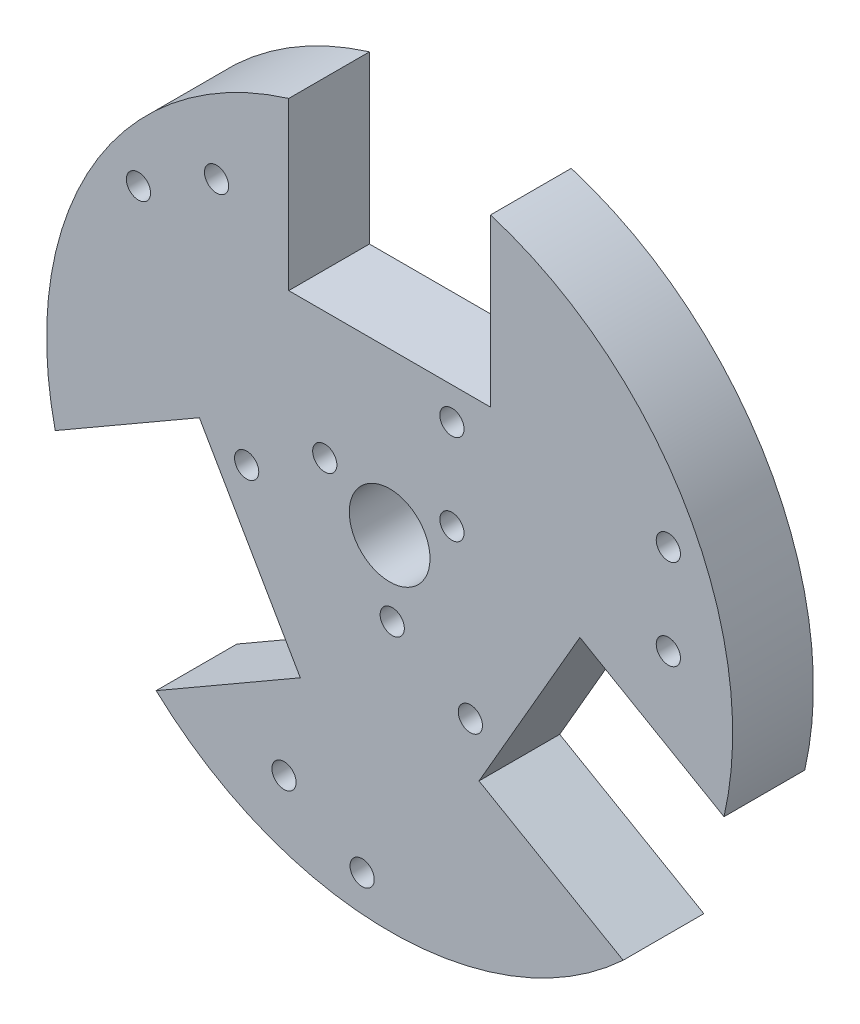
SolidWorks part; units mm, degrees
ref_plane "Front Plane" through (0, 0, 0) normal (0, 0, 1) x (1, 0, 0)
ref_plane "Top Plane" through (0, 0, 0) normal (0, 1, 0) x (1, 0, 0)
ref_plane "Right Plane" through (0, 0, 0) normal (1, 0, 0) x (0, 0, -1)
sketch "Plan" plane through (0, 0, 0) normal (0, 0, 1) x (1, 0, 0)
  line L0 (0, 0) -> (0, 60) construction
  line L1 (0, 0) -> (51.9615, -30) construction
  line L2 (0, 0) -> (-51.9615, -30) construction
  line L3 (0, 0) -> (0, 60) construction
  line L4 (0, 0) -> (51.9615, -30) construction
  line L5 (42.3527, 42.5) -> (-42.3527, 42.5) construction
  line L6 (-10, 60) -> (10, 60)
  line L7 (-10, 60) -> (-10, 25)
  line L8 (-10, 25) -> (10, 25)
  line L9 (10, 60) -> (10, 25)
  circle A0 centre (0, 0) radius 60
  text T0 "Tyre"
  point P13 (0, 60)
  point P17 (-10, 42.5)
  dimension "D1" = 3
  dimension "D5" = 120
  dimension "D2" = 120
  dimension "D3" = 35
  dimension "D4" = 20
sketch "Stepper Motor" plane through (0, 0, 0) normal (0, 0, 1) x (1, 0, 0)
  line L1 (10.7429, 49.5) -> (29.7429, 49.5)
  line L2 (10.7429, 49.5) -> (10.7429, 21.5)
  line L3 (10.7429, 21.5) -> (29.7429, 21.5)
  line L4 (29.7429, 49.5) -> (29.7429, 21.5)
  line L5 (10.7429, 47) -> (0.7429, 47)
  line L6 (10.7429, 47) -> (10.7429, 38)
  line L7 (10.7429, 38) -> (0.7429, 38)
  line L8 (0.7429, 47) -> (0.7429, 38)
  line L9 (-1.5598, 42.5) -> (29.7429, 42.5) construction
  line L11 (42.3527, 42.5) -> (-42.3527, 42.5) construction
  text T0 "Stepper"
  point P11 (0.7429, 42.5)
  dimension "D1" = 28
  dimension "D2" = 19
  dimension "D3" = 9
  dimension "D4" = 10
  dimension "D5" = 2.5
sketch "DC Motor" plane through (0, 0, 0) normal (0, 0, 1) x (1, 0, 0)
  line L0 (63.4697, 76.7537) -> (25.6249, 76.7537) construction
  line L1 (38.6689, 84.3037) -> (63.6689, 84.3037)
  line L2 (38.6689, 84.3037) -> (38.6689, 69.2037)
  line L3 (38.6689, 69.2037) -> (63.6689, 69.2037)
  line L4 (63.6689, 84.3037) -> (63.6689, 69.2037)
  line L5 (28.6689, 79.8287) -> (38.6689, 79.8287)
  line L6 (28.6689, 79.8287) -> (28.6689, 73.6787)
  line L7 (28.6689, 73.6787) -> (38.6689, 73.6787)
  line L8 (38.6689, 79.8287) -> (38.6689, 73.6787)
  text T0 "DC"
  point P10 (38.6689, 76.7537)
  point P11 (38.6689, 76.7537)
  dimension "D1" = 25
  dimension "D2" = 15.1
  dimension "D3" = 10
  dimension "D4" = 6.15
sketch "Sketch4" plane through (0, 0, 0) normal (0, 0, 1) x (1, 0, 0)
  circle A0 centre (0, 0) radius 42.5
  dimension "D1" = 85
extrude "base" add sketch "Sketch4" along normal blind 10
sketch "Sketch5" plane through (0, 0, 0) normal (0, 0, 1) x (1, 0, 0)
  line L0 (0, 0) -> (0, 60) construction
  line L1 (12.5, 20) -> (-12.5, 20)
  line L2 (12.5, 20) -> (12.5, 60)
  line L3 (12.5, 60) -> (-12.5, 60)
  line L4 (-12.5, 20) -> (-12.5, 60)
  line L5 (11.0705, -20.8253) -> (23.5705, 0.8253)
  line L6 (23.5705, 0.8253) -> (58.2115, -19.1747)
  line L7 (11.0705, -20.8253) -> (45.7115, -40.8253)
  line L8 (45.7115, -40.8253) -> (58.2115, -19.1747)
  line L9 (-23.5705, 0.8253) -> (-11.0705, -20.8253)
  line L10 (-11.0705, -20.8253) -> (-45.7115, -40.8253)
  line L11 (-23.5705, 0.8253) -> (-58.2115, -19.1747)
  line L12 (-58.2115, -19.1747) -> (-45.7115, -40.8253)
  circle A0 centre (0, 0) radius 5
  point P4 (0, 20)
  point P7 (0, 60)
  point P19 (0, 0)
  dimension "D1" = 25
  dimension "D2" = 40
  dimension "D4" = 20
  dimension "D3" = 3
extrude "Tyre cut" cut sketch "Sketch5" along normal blind 10
sketch "arm" plane through (0, 0, 0) normal (0, 0, 1) x (1, 0, 0)
  line L0 (-12.5, 20) -> (12.5, 20) construction
  line L1 (12.5, 49.5) -> (29.7429, 49.5)
  line L2 (12.5, 49.5) -> (12.5, 0.8253)
  line L3 (12.5, 0.8253) -> (29.7429, 0.8253)
  line L4 (29.7429, 49.5) -> (29.7429, 0.8253)
  line L5 (4.9314, 20) -> (37.5, 20)
  line L6 (12.5, 20) -> (12.5, 40.6202) construction
  line L7 (29.7429, 49.5) -> (29.7429, 21.5) construction
  line L8 (10.7429, 49.5) -> (29.7429, 49.5) construction
  line L9 (-5.5353, -11.238) -> (-14.1567, -26.1707)
  line L10 (27.9968, -50.5081) -> (-14.1567, -26.1707)
  line L11 (36.6183, -35.5753) -> (-5.5353, -11.238)
  line L12 (36.6183, -35.5753) -> (27.9968, -50.5081)
  line L13 (-6.9647, 10.4127) -> (-15.5862, 25.3454)
  line L14 (-57.7397, 1.0081) -> (-15.5862, 25.3454)
  line L15 (-49.1183, -13.9247) -> (-6.9647, 10.4127)
  line L16 (-49.1183, -13.9247) -> (-57.7397, 1.0081)
  line L17 (4.9314, 20) -> (4.9314, 0.8253)
  line L18 (4.9314, 0.8253) -> (37.5, 0.8253)
  line L19 (37.5, 20) -> (37.5, 0.8253)
  line L20 (14.8548, -14.2707) -> (-1.751, -4.6834)
  line L21 (-1.751, -4.6834) -> (-18.0353, -32.8886)
  line L22 (14.8548, -14.2707) -> (-1.4295, -42.476)
  line L23 (-1.4295, -42.476) -> (-18.0353, -32.8886)
  line L24 (-19.7862, -5.7293) -> (-3.1805, 3.8581)
  line L25 (-3.1805, 3.8581) -> (-19.4647, 32.0633)
  line L26 (-19.7862, -5.7293) -> (-36.0705, 22.476)
  line L27 (-36.0705, 22.476) -> (-19.4647, 32.0633)
  line L29 (10.5, 20) -> (31.7429, 20)
  line L30 (10.5, 20) -> (10.5, 0.8253)
  line L31 (10.5, 0.8253) -> (31.7429, 0.8253)
  line L32 (31.7429, 20) -> (31.7429, 0.8253)
  line L33 (12.0705, -19.0933) -> (-4.5353, -9.5059)
  line L34 (1.4491, -37.4901) -> (-15.1567, -27.9028)
  line L35 (-22.5705, -0.9067) -> (-5.9647, 8.6806)
  line L36 (-33.1919, 17.4901) -> (-16.5862, 27.0775)
  circle A0 centre (0, 0) radius 5 construction
  arc A1 (41.4281, -9.4848) -> (12.5, 40.6202) centre (0, 0) ccw construction
  point P21 (0, 0)
  point P37 (0, 0)
  point P50 (0, 0)
  dimension "D5" = 2
  dimension "D6" = 2
  dimension "D1" = 3
  dimension "D4" = 3
  dimension "D7" = 3
sketch "Sketch6" plane through (0, 0, 0) normal (0, 0, 1) x (1, 0, 0)
  line L1 (21.1214, 16.9548) -> (21.1214, 5.6527) construction
  line L2 (4.9314, 18.6632) -> (10.5, 18.6632) construction
  line L3 (4.9314, 20) -> (4.9314, 0.8253) construction
  line L4 (10.5, 20) -> (10.5, 0.8253) construction
  line L5 (4.9314, 20) -> (37.5, 20) construction
  line L6 (4.9314, 0.8253) -> (37.5, 0.8253) construction
  line L7 (12.5, 0.8253) -> (29.7429, 0.8253) construction
  circle A0 centre (7.7157, 16) radius 1.5
  circle A1 centre (7.7157, 4.8253) radius 1.5
  circle A2 centre (34.5272, 4.8253) radius 1.5
  circle A3 centre (34.5272, 16) radius 1.5
  circle A4 centre (9.9986, -14.682) radius 1.5
  circle A5 centre (0.321, -9.0947) radius 1.5
  circle A6 centre (-13.0847, -32.3141) radius 1.5
  circle A7 centre (-3.4072, -37.9014) radius 1.5
  circle A8 centre (-17.7143, -1.318) radius 1.5
  circle A9 centre (-8.0367, 4.2693) radius 1.5
  circle A10 centre (-21.4424, 27.4887) radius 1.5
  circle A11 centre (-31.12, 21.9014) radius 1.5
  point P11 (7.7157, 18.6632)
  point P19 (21.1214, 0.8253)
  point P43 (0, 0)
  point P44 (0, 0)
  dimension "D1" = 4
  dimension "D2" = 4
  dimension "D3" = 3
extrude "NUTs" cut sketch "Sketch6" along normal blind 10
